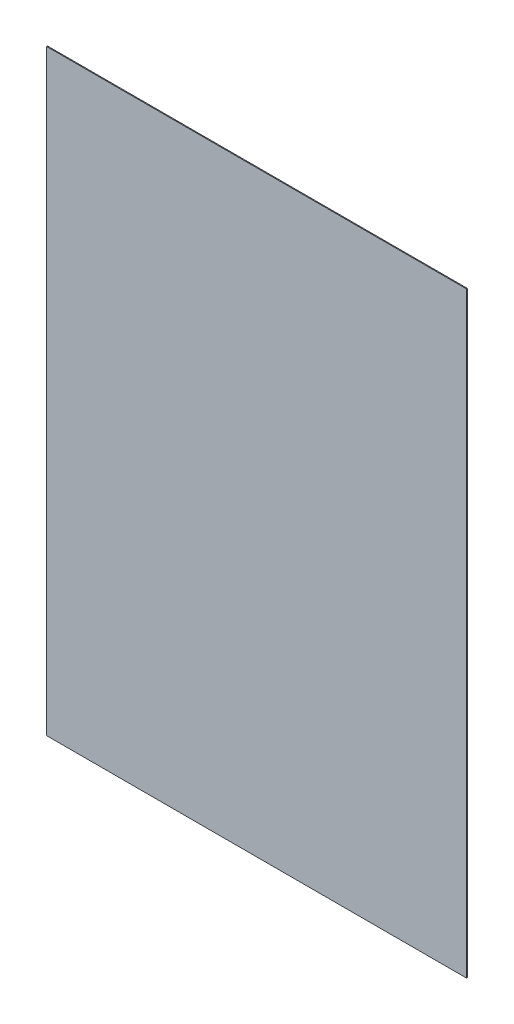
SolidWorks part; units mm, degrees
ref_plane "Alzado" through (0, 0, 0) normal (0, 0, 1) x (1, 0, 0)
ref_plane "Planta" through (0, 0, 0) normal (0, 1, 0) x (1, 0, 0)
ref_plane "Vista lateral" through (0, 0, 0) normal (1, 0, 0) x (0, 0, -1)
sketch "Croquis1" plane through (0, 0, 0) normal (0, 0, 1) x (1, 0, 0)
  line L1 (-450, 640) -> (450, 640)
  line L2 (-450, 640) -> (-450, -640)
  line L3 (-450, -640) -> (450, -640)
  line L4 (450, 640) -> (450, -640)
  line L5 (-450, 640) -> (450, -640) construction
  line L6 (-450, -640) -> (450, 640) construction
  point P0 (0, 0)
  dimension "D1" = 900
  dimension "D2" = 1280
extrude "Saliente-Extruir1" add sketch "Croquis1" along normal blind 1.9
